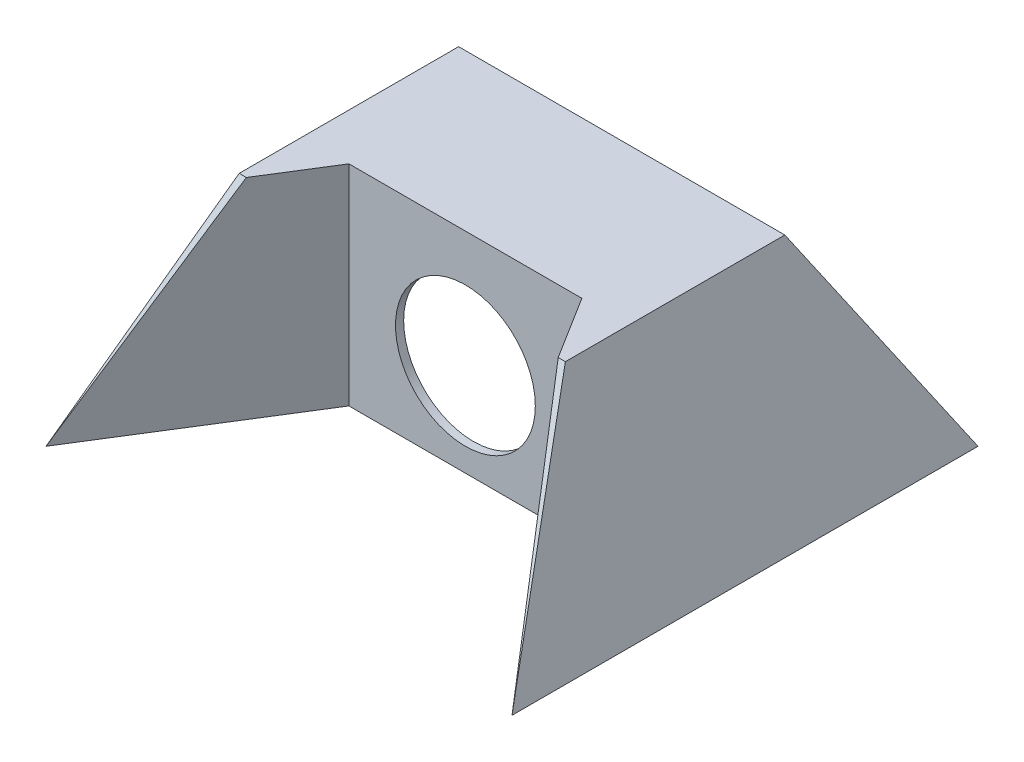
SolidWorks part; units mm, degrees
ref_plane "Ebene vorne" through (0, 0, 0) normal (0, 0, 1) x (1, 0, 0)
ref_plane "Ebene oben" through (0, 0, 0) normal (0, 1, 0) x (1, 0, 0)
ref_plane "Ebene rechts" through (0, 0, 0) normal (1, 0, 0) x (0, 0, -1)
sketch "Skizze1" plane through (0, 0, 0) normal (0, 0, 1) x (1, 0, 0)
  line L0 (0, 0) -> (100, 0)
  line L1 (100, 0) -> (85, 45)
  line L2 (85, 45) -> (15, 45)
  line L3 (15, 45) -> (0, 0)
  dimension "D1" = 100
  dimension "D2" = 15
  dimension "D3" = 15
  dimension "D4" = 45
extrude "Grundkörper" add sketch "Skizze1" against normal blind 100
sketch "Skizze2" plane through (0, 0, 0) normal (1, 0, 0) x (0, 0, -1)
  line L0 (100, 0) -> (73.5442, 45)
  line L1 (100, 45) -> (0, 45) construction
  line L2 (73.5442, 45) -> (100, 45)
  line L3 (100, 45) -> (100, 0)
extrude "Schraegen_vorne" cut sketch "Skizze2" along normal blind 100
ref_plane "Ebene1" through (0, 0, -50) normal (0, 0, 1) x (1, 0, 0)
mirror "Spiegel_Schraege_hinten" about plane through (0, 0, -50) normal (0, 0, 1) of "Schraegen_vorne"
sketch "Skizze4" plane through (0, 0, 0) normal (0, -1, 0) x (1, 0, 0)
  line L0 (100, 0) -> (75, -40)
  line L1 (75, -40) -> (25, -40)
  line L2 (25, -40) -> (0, 0)
  line L3 (0, 0) -> (100, 0)
  dimension "D1" = 50
  dimension "D2" = 25
  dimension "D3" = 40
extrude "Schnitt-Linear austragen4" cut sketch "Skizze4" against normal blind 45
sketch "Skizze6" plane through (0, 0, -40) normal (0, 0, 1) x (1, 0, 0)
  circle A0 centre (50, 20) radius 15
shell "Wandung3" thickness 1.75
extrude "Schnitt-Linear austragen6" cut sketch "Skizze6" against normal blind 2 contours A0
ref_plane "Ebene2" through (0, 0, -50) normal (0, 0, 1) x (1, 0, 0)
sketch "Skizze7" plane through (0, 0, -50) normal (0, 0, 1) x (1, 0, 0)
  circle A0 centre (50, 20) radius 0.5
